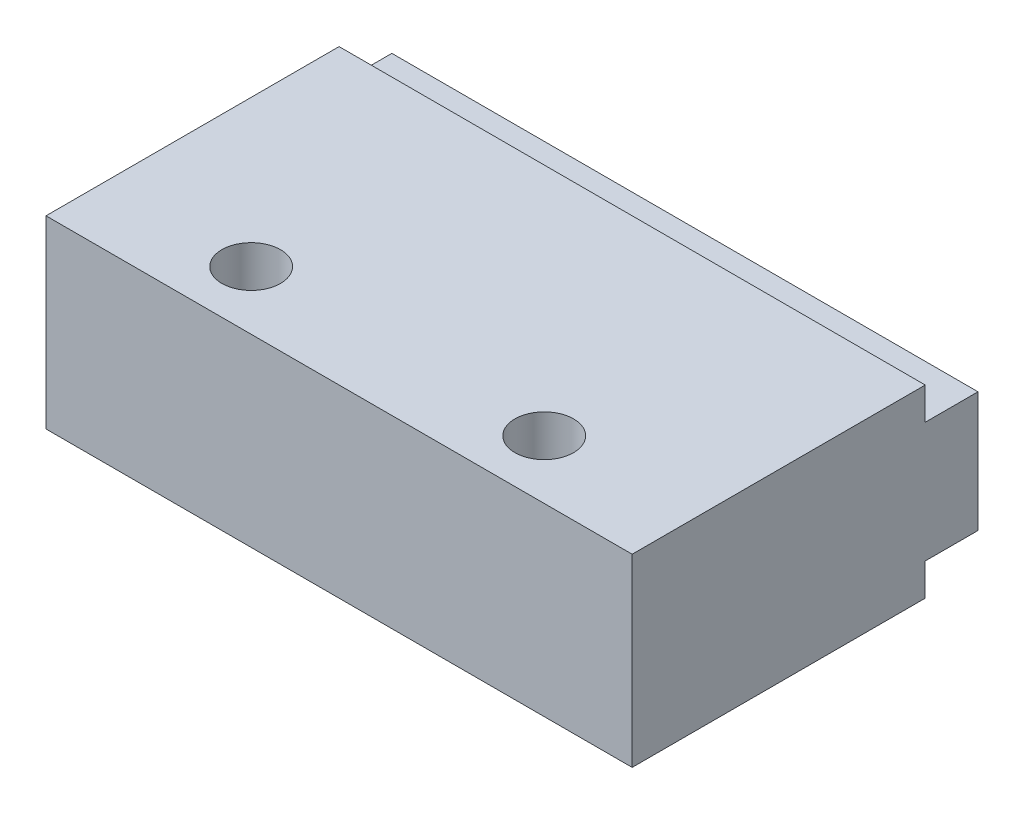
SolidWorks part; units mm, degrees
ref_plane "Front Plane" through (0, 0, 0) normal (0, 0, 1) x (1, 0, 0)
ref_plane "Top Plane" through (0, 0, 0) normal (0, 1, 0) x (1, 0, 0)
ref_plane "Right Plane" through (0, 0, 0) normal (1, 0, 0) x (0, 0, -1)
sketch "Sketch1" plane through (0, 0, 0) normal (0, 1, 0) x (1, 0, 0)
  line L1 (0, 0) -> (20, 0)
  line L2 (0, 0) -> (0, 10)
  line L3 (0, 10) -> (20, 10)
  line L4 (20, 0) -> (20, 10)
  dimension "D1" = 20
  dimension "D2" = 10
extrude "Boss-Extrude1" add sketch "Sketch1" along normal blind 6.3
sketch "Sketch2" plane through (0, 0, -10) normal (0, 0, -1) x (-1, 0, 0)
  line L0 (-20, 6.3) -> (-20, 0) construction
  line L1 (-20, 5.2) -> (0, 5.2)
  line L2 (-20, 5.2) -> (-20, 1.1)
  line L3 (-20, 1.1) -> (0, 1.1)
  line L4 (0, 5.2) -> (0, 1.1)
  line L5 (0, 6.3) -> (0, 0) construction
  line L6 (-20, 3.15) -> (0, 3.15) construction
  dimension "D1" = 4.1
  dimension "D2" = 2.05
extrude "Boss-Extrude2" add sketch "Sketch2" along normal blind 1.8
sketch "Sketch3" plane through (0, 6.3, 0) normal (0, 1, 0) x (1, 0, 0)
  line L0 (0, 2) -> (20, 2) construction
  line L1 (0, 10) -> (0, 0) construction
  line L2 (20, 0) -> (20, 10) construction
  line L3 (0, 10) -> (20, 10) construction
  line L4 (10, 10) -> (10, 0) construction
  line L5 (0, 0) -> (20, 0) construction
  circle A0 centre (5, 2) radius 1
  circle A1 centre (15, 2) radius 1
  point P16 (0, 0)
  dimension "D2" = 2
  dimension "D3" = 2
  dimension "D1" = 8
  dimension "D4" = 10
extrude "Cut-Extrude1" cut sketch "Sketch3" against normal through all
